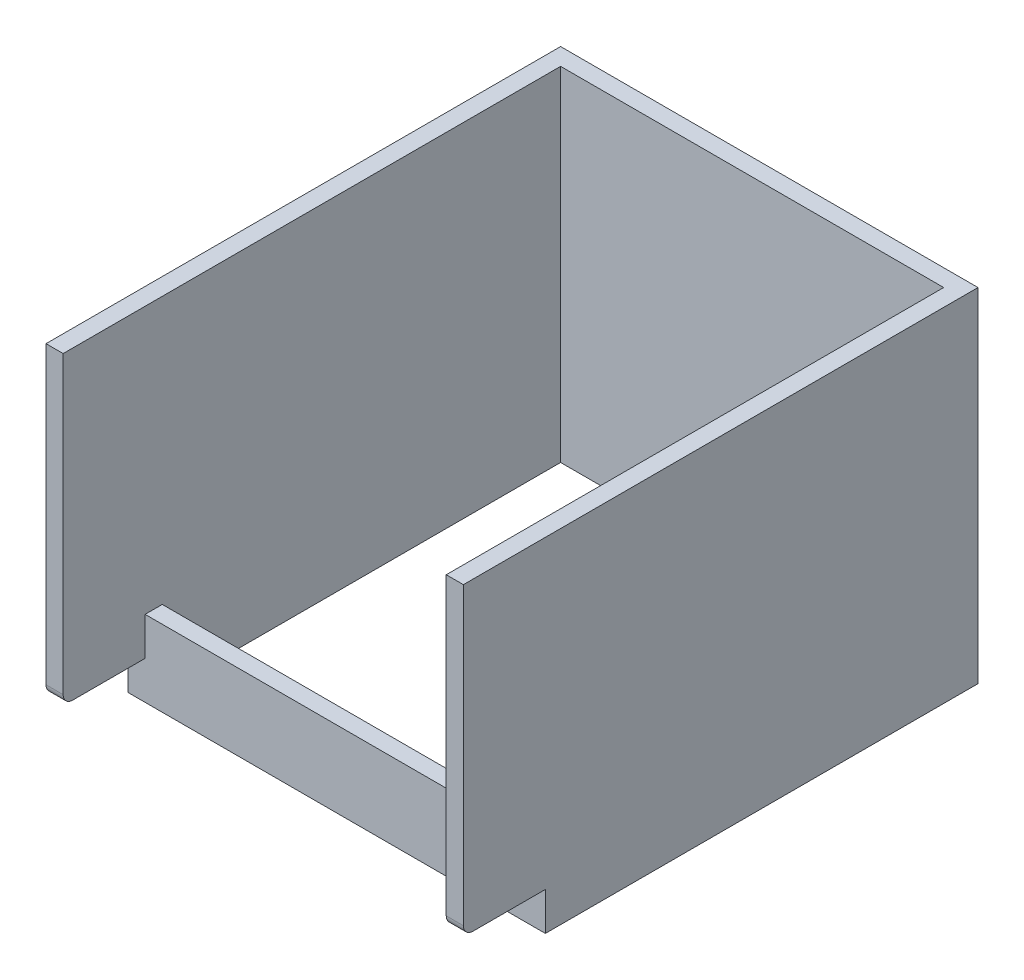
SolidWorks part; units mm, degrees
material "Custom Plastic"
ref_plane "Front Plane" through (0, 0, 0) normal (0, 0, 1) x (1, 0, 0)
ref_plane "Top Plane" through (0, 0, 0) normal (0, 1, 0) x (1, 0, 0)
ref_plane "Right Plane" through (0, 0, 0) normal (1, 0, 0) x (0, 0, -1)
sketch "Sketch1" plane through (0, 0, 0) normal (0, 1, 0) x (1, 0, 0)
  line L1 (-109.5, -125) -> (109.5, -125)
  line L2 (-109.5, -125) -> (-109.5, 125)
  line L3 (-109.5, 125) -> (109.5, 125)
  line L4 (109.5, -125) -> (109.5, 125)
  line L5 (-109.5, -125) -> (109.5, 125) construction
  line L6 (-109.5, 125) -> (109.5, -125) construction
  point P0 (0, 0)
extrude "Boss-Extrude1" add sketch "Sketch1" along normal blind 3
sketch "Sketch2" plane through (0, 0, 0) normal (0, 1, 0) x (1, 0, 0)
  line L0 (-109.5, -125) -> (-109.5, 125)
  line L1 (-109.5, 125) -> (109.5, 125)
  line L2 (109.5, 125) -> (109.5, -125)
  line L3 (109.5, -125) -> (109.5, -145)
  line L4 (-109.5, -125) -> (-109.5, -145)
extrude "Extrude-Thin1" add sketch "Sketch2" along normal blind 180 thin
sketch "Sketch4" plane through (0, 0, 0) normal (1, 0, 0) x (0, 0, -1)
  line L1 (-167.9331, 0) -> (-102, 0)
  line L2 (-167.9331, 0) -> (-167.9331, 20)
  line L3 (-167.9331, 20) -> (-102, 20)
  line L4 (-102, 0) -> (-102, 20)
extrude "Cut-Extrude2" cut sketch "Sketch4" against normal through all both and the other way through all
sketch "Sketch7" plane through (0, 0, 0) normal (0, 1, 0) x (1, 0, 0)
  line L5 (100.5, -102) -> (100.5, 116) construction
  line L6 (-100.5, -102) -> (100.5, -102)
  line L7 (-100.5, -102) -> (-100.5, -93)
  line L8 (-100.5, -93) -> (100.5, -93)
  line L9 (100.5, -102) -> (100.5, -93)
extrude "Boss-Extrude3" add sketch "Sketch7" along normal blind 40
fillet "Fillet7" radius 5 2 edges at (-105, 20, 145) (105, 20, 145)
sketch "Sketch8" plane through (0, 0, 0) normal (0, 1, 0) x (1, 0, 0)
  line L1 (-100.5, 116) -> (100.5, 116)
  line L2 (-100.5, 116) -> (-100.5, -93)
  line L3 (-100.5, -93) -> (100.5, -93)
  line L4 (100.5, 116) -> (100.5, -93)
extrude "Cut-Extrude3" cut sketch "Sketch8" along normal blind 20
